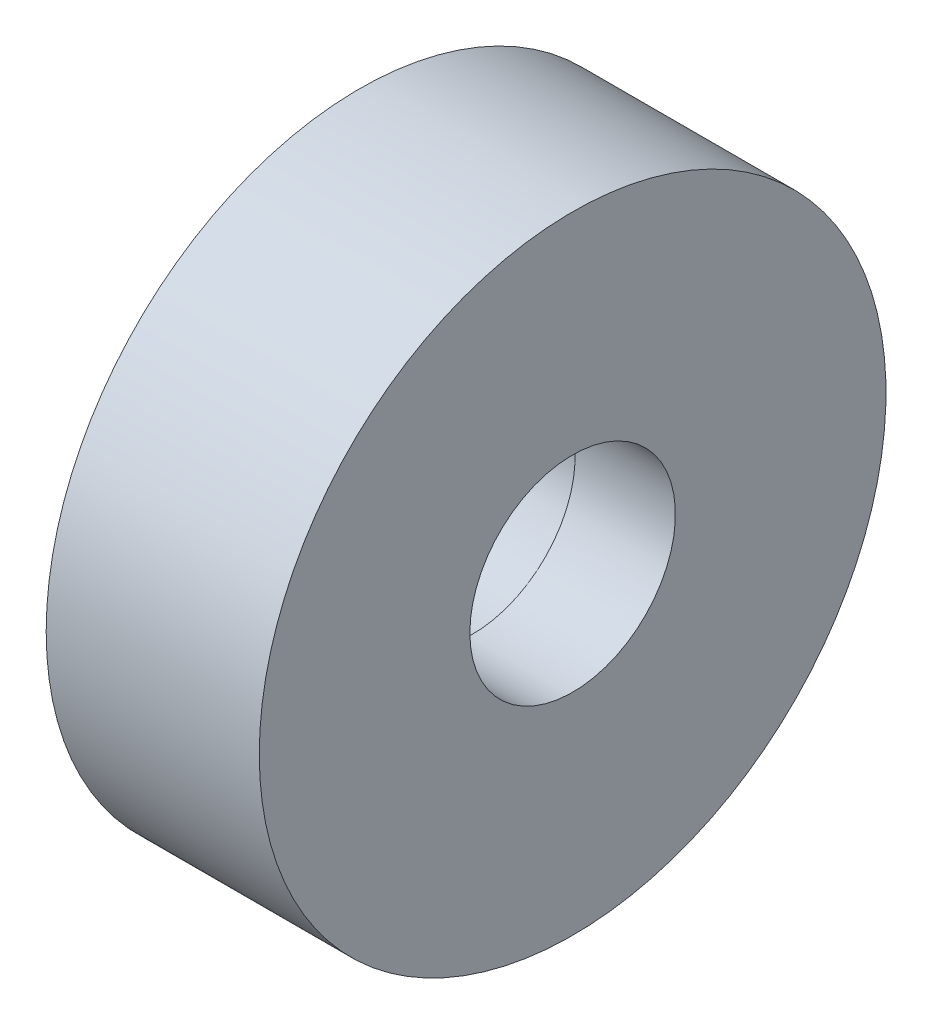
SolidWorks part; units mm, degrees
ref_plane "Front Plane" through (0, 0, 0) normal (0, 0, 1) x (1, 0, 0)
ref_plane "Top Plane" through (0, 0, 0) normal (0, 1, 0) x (1, 0, 0)
ref_plane "Right Plane" through (0, 0, 0) normal (1, 0, 0) x (0, 0, -1)
sketch "Sketch1" plane through (0, 0, 0) normal (0, 0, 1) x (1, 0, 0)
  line L0 (0, 0) -> (5.1881, 0) construction
  line L2 (-4.25, 1.625) -> (-4.25, 12.5) construction
  line L3 (-4.25, 12.5) -> (4.25, 12.5)
  line L4 (4.25, 4.1) -> (4.25, 12.5)
  line L5 (-4.25, 12.5) -> (-4.25, 4.15)
  line L6 (-4.25, 4.15) -> (0.25, 4.15)
  line L8 (0.25, 4.1) -> (4.25, 4.1)
  line L11 (0.25, 4.15) -> (0.25, 4.1)
  dimension "D1" = 12.5
  dimension "D2" = 8.5
  dimension "D3" = 4.15
  dimension "D4" = 4.25
  dimension "D5" = 4.1
  dimension "D6" = 4
revolve "Revolve1" add sketch "Sketch1" angle 360 about L0
